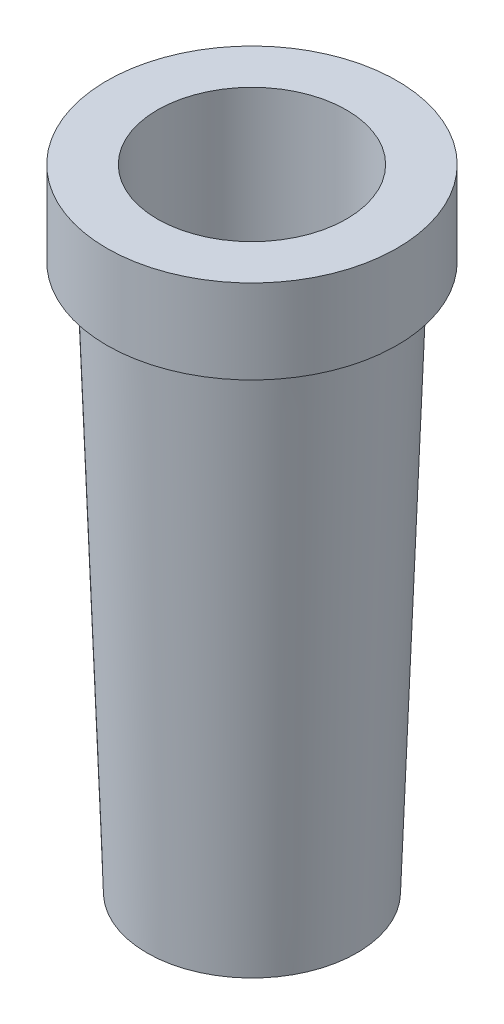
SolidWorks part; units mm, degrees
ref_plane "Front Plane" through (0, 0, 0) normal (0, 0, 1) x (1, 0, 0)
ref_plane "Top Plane" through (0, 0, 0) normal (0, 1, 0) x (1, 0, 0)
ref_plane "Right Plane" through (0, 0, 0) normal (1, 0, 0) x (0, 0, -1)
sketch "Sketch1" plane through (0, 0, 0) normal (0, 0, 1) x (1, 0, 0)
  line L0 (0, 0) -> (2.5, 0)
  line L1 (2.5, 0) -> (2.954, 13)
  line L2 (2.954, 13) -> (3.454, 13)
  line L3 (3.454, 13) -> (3.454, 15)
  line L4 (3.454, 15) -> (0, 15)
  line L5 (0, 15) -> (0, 0)
  dimension "D1" = 15
  dimension "D2" = 2.5
  dimension "D3" = 2
  dimension "D4" = 0.5
  dimension "D5" = 92
revolve "Revolve1" add sketch "Sketch1" angle 360 about L5
hole_wizard "M4 Clearance Hole1" positions "Sketch2" profile "Sketch3" hole size "M4" standard "ISO" end condition through all
sketch "Sketch2" plane through (0, 15, 0) normal (0, 1, 0) x (1, 0, 0)
  point P0 (0, 0)
sketch "Sketch3" plane through (0, 15, 0) normal (1, 0, 0) x (0, 0, 1)
  line L0 (0, 0) -> (0, 15)
  line L1 (0, 15) -> (2.25, 15)
  line L2 (2.25, 15) -> (2.25, 0)
  line L5 (2.25, 0) -> (0, 0)
  line L11 (0, -6.35) -> (0, 107.95) construction
  dimension "Thru Hole Dia." = 4.5
  dimension "Thru Hole Depth" = 15
